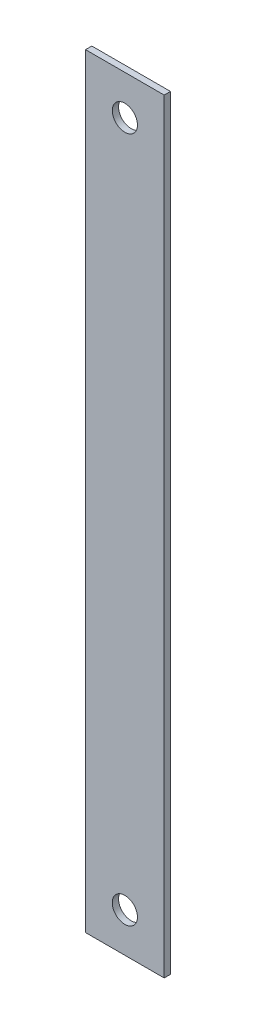
SolidWorks part; units mm, degrees
ref_plane "Front Plane" through (0, 0, 0) normal (0, 0, 1) x (1, 0, 0)
ref_plane "Top Plane" through (0, 0, 0) normal (0, 1, 0) x (1, 0, 0)
ref_plane "Right Plane" through (0, 0, 0) normal (1, 0, 0) x (0, 0, -1)
sketch "Sketch1" plane through (0, 0, 0) normal (0, 0, 1) x (1, 0, 0)
  line L0 (-12.5, 0) -> (12.5, 0) construction
  line L1 (3.5, 121.5) -> (12.5, 121.5)
  line L2 (-12.5, 112.5) -> (-12.5, -105.5)
  line L3 (3.5, -121.5) -> (12.5, -121.5)
  line L4 (12.5, 121.5) -> (12.5, -121.5)
  line L5 (-12.5, 121.5) -> (12.5, -121.5) construction
  line L6 (-12.5, -121.5) -> (12.5, 121.5) construction
  line L7 (-12.5, 112.5) -> (-12.5, 121.5) construction
  line L8 (-12.5, 121.5) -> (3.5, 121.5) construction
  line L9 (-12.5, 112.5) -> (-12.5, 121.5) construction
  line L10 (-12.5, 112.5) -> (-12.5, 121.4821)
  line L11 (3.5, 121.5) -> (0, 121.5)
  line L12 (-12.5, -105.5) -> (-12.5, -115.4875)
  line L13 (3.5, -121.5) -> (0, -121.5)
  line L14 (-12.5, 121.4821) -> (-12.5, 121.5)
  line L15 (-12.5, 121.5) -> (0, 121.5)
  line L16 (-12.5, -115.4875) -> (-12.5, -121.5)
  line L17 (-12.5, -121.5) -> (0, -121.5)
  circle A0 centre (0, 109) radius 4
  circle A1 centre (0, -109) radius 4
  point P0 (0, 0)
  point P14 (-12.5, 121.4821)
  dimension "D4" = 8
  dimension "D1" = 25
  dimension "D3" = 218
  dimension "D6" = 243
extrude "Boss-Extrude1" add sketch "Sketch1" along normal blind 2
